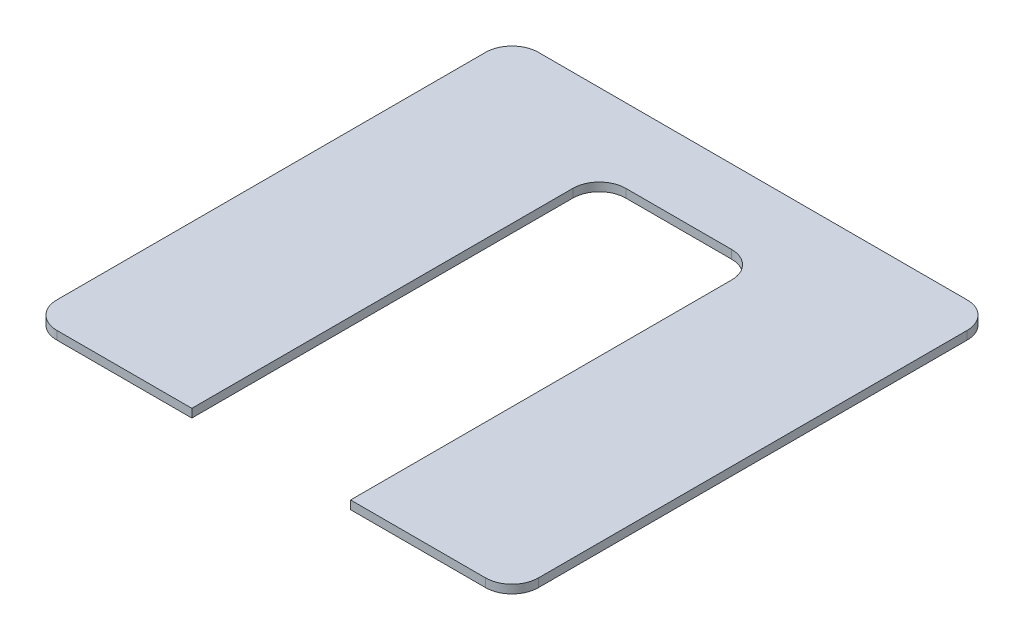
SolidWorks part; units mm, degrees
ref_plane "Front Plane" through (0, 0, 0) normal (0, 0, 1) x (1, 0, 0)
ref_plane "Top Plane" through (0, 0, 0) normal (0, 1, 0) x (1, 0, 0)
ref_plane "Right Plane" through (0, 0, 0) normal (1, 0, 0) x (0, 0, -1)
sketch "Sketch1" plane through (0, 0, 0) normal (0, 1, 0) x (1, 0, 0)
  line L1 (-45.5, -45.5) -> (45.5, -45.5)
  line L2 (-45.5, -45.5) -> (-45.5, 45.5)
  line L3 (-45.5, 45.5) -> (45.5, 45.5)
  line L4 (45.5, -45.5) -> (45.5, 45.5)
  line L5 (-45.5, -45.5) -> (45.5, 45.5) construction
  line L6 (-45.5, 45.5) -> (45.5, -45.5) construction
  point P0 (0, 0)
  dimension "D1" = 91
extrude "Boss-Extrude1" add sketch "Sketch1" along normal blind 1.6 contours L1 L4 L3 L2
sketch "Sketch2" plane through (0, 1.6, 0) normal (0, 1, 0) x (1, 0, 0)
  line L0 (-45.5, -45.5) -> (45.5, -45.5) construction
  line L1 (-15, 31.5) -> (15, 31.5)
  line L2 (-15, 31.5) -> (-15, -45.5)
  line L3 (-15, -45.5) -> (15, -45.5)
  line L4 (15, 31.5) -> (15, -45.5)
  line L5 (-15, 31.5) -> (15, -45.5) construction
  line L6 (-15, -45.5) -> (15, 31.5) construction
  point P0 (0, -7)
  dimension "D1" = 30
  dimension "D2" = 77
extrude "Cut-Extrude1" cut sketch "Sketch2" against normal through all
fillet "Fillet1" radius 5 6 edges at (-45.5, 0.8, -45.5) (-45.5, 0.8, 45.5) (45.5, 0.8, 45.5) (45.5, 0.8, -45.5) (15, 0.8, -31.5) (-15, 0.8, -31.5)
